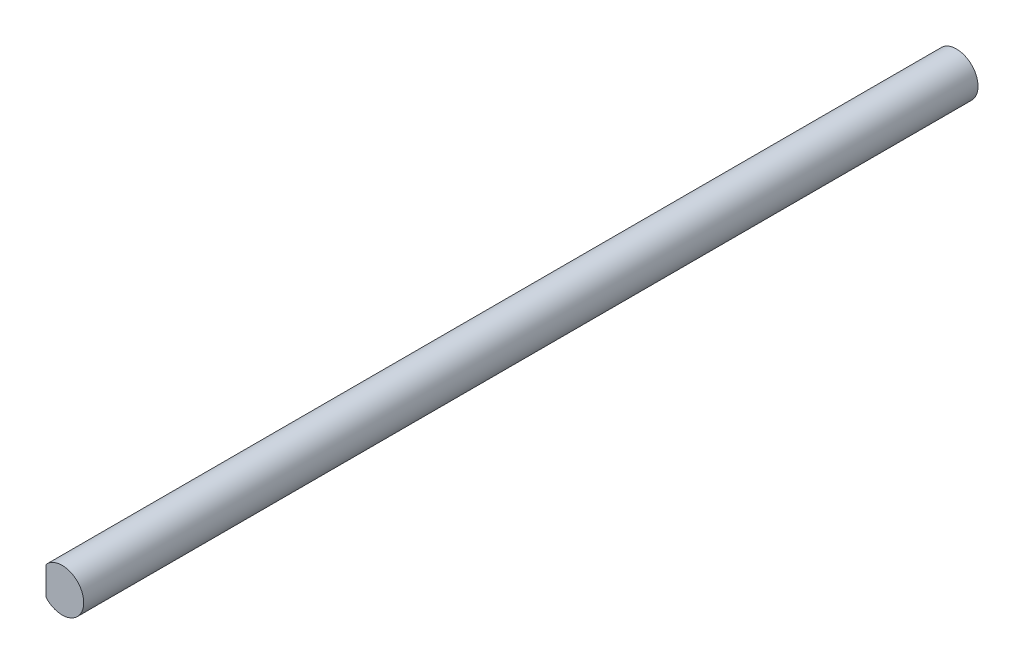
SolidWorks part; units mm, degrees
ref_plane "Front Plane" through (0, 0, 0) normal (0, 0, 1) x (1, 0, 0)
ref_plane "Top Plane" through (0, 0, 0) normal (0, 1, 0) x (1, 0, 0)
ref_plane "Right Plane" through (0, 0, 0) normal (1, 0, 0) x (0, 0, -1)
sketch "Sketch1" plane through (0, 0, 0) normal (0, 0, 1) x (1, 0, 0)
  circle A0 centre (0, 0) radius 4
extrude "Axle_166mm" add sketch "Sketch1" along normal blind 166 from offset 0
sketch "Sketch2" plane through (0, 0, 0) normal (0, 0, 1) x (1, 0, 0)
  line L1 (-5, -5) -> (-3, -5)
  line L2 (-5, -5) -> (-5, 5)
  line L3 (-5, 5) -> (-3, 5)
  line L4 (-3, -5) -> (-3, 5)
extrude "Print_Bed_Flat_1mm" cut sketch "Sketch2" along normal blind 166.2 from offset 0.1
